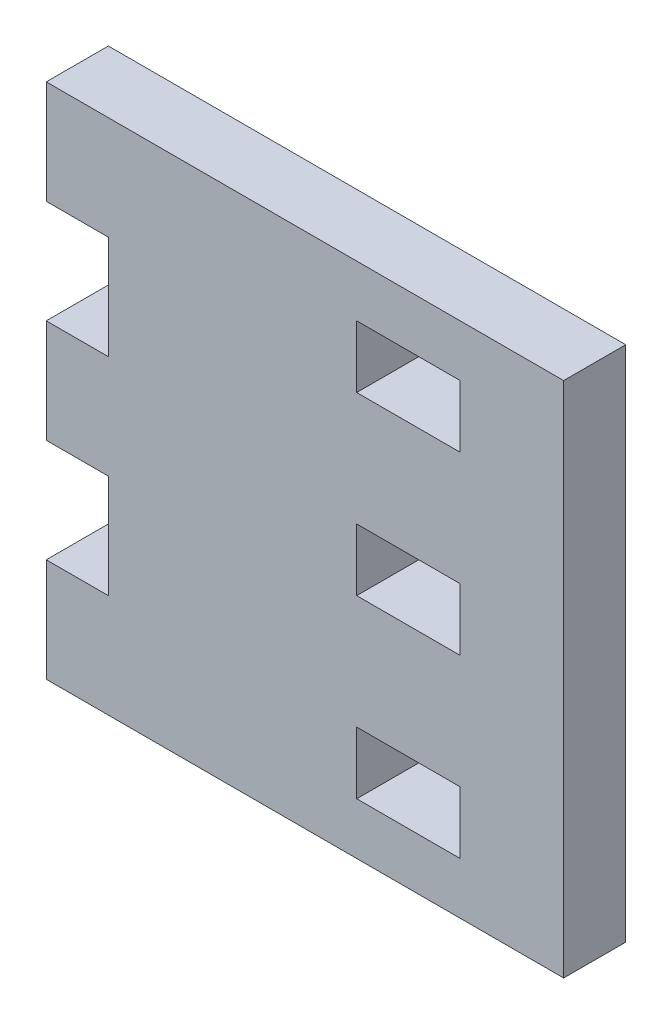
SolidWorks part; units mm, degrees
ref_plane "前基準面" through (0, 0, 0) normal (0, 0, 1) x (1, 0, 0)
ref_plane "上基準面" through (0, 0, 0) normal (0, 1, 0) x (1, 0, 0)
ref_plane "右基準面" through (0, 0, 0) normal (1, 0, 0) x (0, 0, -1)
sketch "草圖1" plane through (0, 0, 0) normal (0, 0, 1) x (1, 0, 0)
  line L1 (-26.3629, 32.7637) -> (23.6371, 32.7637)
  line L2 (-26.3629, 32.7637) -> (-26.3629, 22.7637)
  line L3 (-26.3629, -17.2363) -> (23.6371, -17.2363)
  line L4 (23.6371, 32.7637) -> (23.6371, -17.2363)
  line L5 (-26.3629, 22.7637) -> (-20.3629, 22.7637)
  line L7 (-26.3629, 12.7637) -> (-20.3629, 12.7637)
  line L8 (-20.3629, 22.7637) -> (-20.3629, 12.7637)
  line L9 (-26.3629, 2.7637) -> (-20.3629, 2.7637)
  line L10 (-20.3629, 2.7637) -> (-20.3629, -7.2363)
  line L11 (-26.3629, -7.2363) -> (-20.3629, -7.2363)
  line L16 (-26.3629, 12.7637) -> (-26.3629, 2.7637)
  line L17 (-26.3629, -7.2363) -> (-26.3629, -17.2363)
  line L19 (3.6371, 10.7637) -> (3.6371, 4.7637)
  line L20 (3.6371, 27.7637) -> (13.6371, 27.7637)
  line L21 (3.6371, 27.7637) -> (3.6371, 21.7637)
  line L22 (3.6371, 21.7637) -> (13.6371, 21.7637)
  line L23 (13.6371, 27.7637) -> (13.6371, 21.7637)
  line L24 (3.6371, 10.7637) -> (13.6371, 10.7637)
  line L25 (13.6371, 10.7637) -> (13.6371, 4.7637)
  line L26 (3.6371, 4.7637) -> (13.6371, 4.7637)
  line L27 (3.6371, -6.2363) -> (3.6371, -12.2363)
  line L28 (3.6371, -6.2363) -> (13.6371, -6.2363)
  line L29 (13.6371, -6.2363) -> (13.6371, -12.2363)
  line L30 (3.6371, -12.2363) -> (13.6371, -12.2363)
  point P8 (-23.3629, 22.7637)
  point P21 (8.6371, 27.7637)
  dimension "D1" = 50
  dimension "D2" = 50
  dimension "D3" = 6
  dimension "D4" = 10
  dimension "D5" = 10
  dimension "D7" = 6
  dimension "D8" = 10
  dimension "D9" = 10
  dimension "D10" = 5
  dimension "D12" = 10
  dimension "D13" = 5
  dimension "D6" = 2
  dimension "D11" = 3
extrude "填料-伸長1" add sketch "草圖1" along normal blind 6
